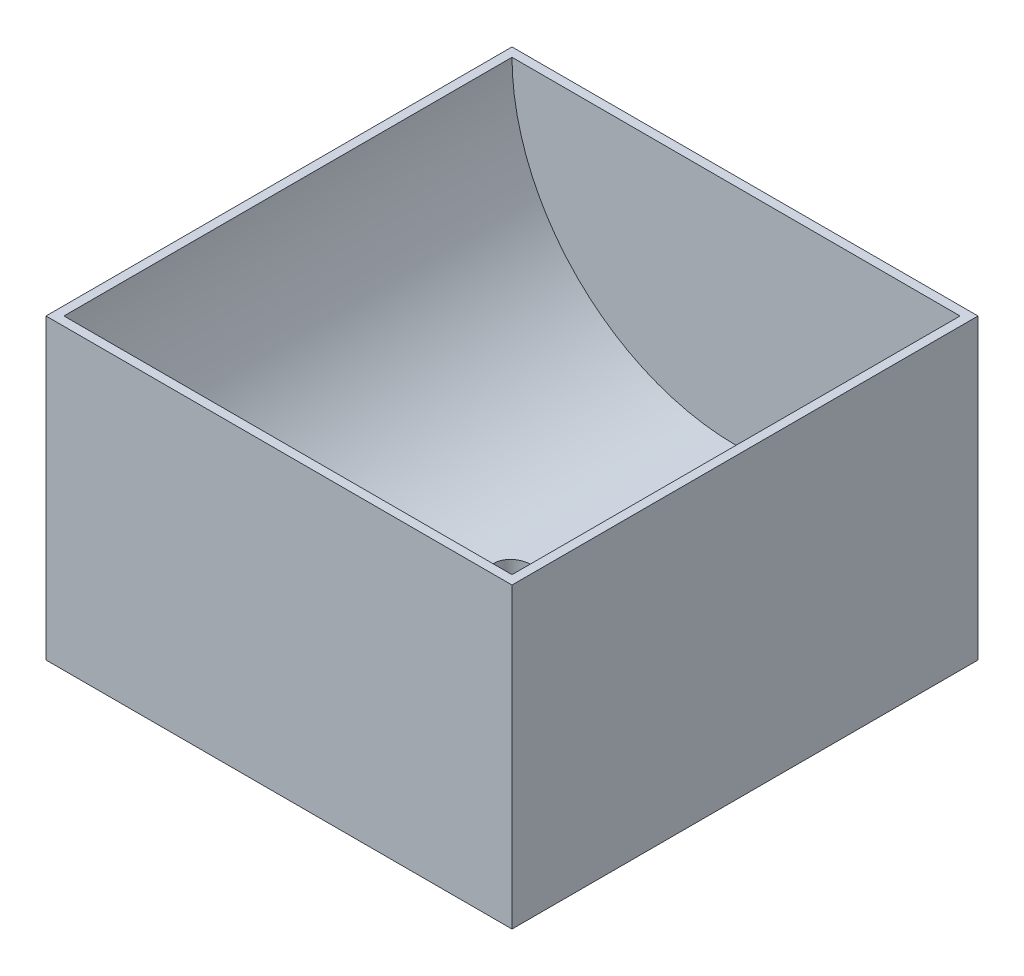
SolidWorks part; units mm, degrees
ref_plane "Front Plane" through (0, 0, 0) normal (0, 0, 1) x (1, 0, 0)
ref_plane "Top Plane" through (0, 0, 0) normal (0, 1, 0) x (1, 0, 0)
ref_plane "Right Plane" through (0, 0, 0) normal (1, 0, 0) x (0, 0, -1)
sketch "Sketch1" plane through (0, 0, 0) normal (0, 0, 1) x (1, 0, 0)
  line L0 (50, 0) -> (52, 0)
  line L1 (-52, 0) -> (-50, 0)
  line L2 (-52, 0) -> (-52, -53)
  line L3 (-52, -53) -> (52, -53)
  line L4 (52, 0) -> (52, -53)
  arc A0 (-50, 0) -> (50, 0) centre (0, 0) ccw
  dimension "D1" = 100
  dimension "D2" = 2
  dimension "D3" = 2
  dimension "D4" = 3
extrude "Boss-Extrude1" add sketch "Sketch1" along normal mid plane 100
sketch "Sketch2" plane through (0, 0, 50) normal (0, 0, 1) x (1, 0, 0)
  line L1 (-52, 0) -> (52, 0)
  line L2 (-52, 0) -> (-52, -53)
  line L3 (-52, -53) -> (52, -53)
  line L4 (52, 0) -> (52, -53)
extrude "Boss-Extrude2" add sketch "Sketch2" along normal blind 2
sketch "Sketch3" plane through (0, 0, -50) normal (0, 0, -1) x (-1, 0, 0)
  line L1 (-52, 0) -> (52, 0)
  line L2 (-52, 0) -> (-52, -53)
  line L3 (-52, -53) -> (52, -53)
  line L4 (52, 0) -> (52, -53)
extrude "Boss-Extrude3" add sketch "Sketch3" along normal blind 2
sketch "Sketch4" plane through (0, -53, 0) normal (0, -1, 0) x (1, 0, 0)
  circle A0 centre (0, 0) radius 4.05
  dimension "D1" = 8.1
extrude "Cut-Extrude2" cut sketch "Sketch4" against normal through all
sketch "Sketch5" plane through (0, -53, 0) normal (0, -1, 0) x (1, 0, 0)
  line L1 (-7.5056, 0) -> (-3.7528, -6.5)
  line L2 (-3.7528, -6.5) -> (3.7528, -6.5)
  line L3 (3.7528, -6.5) -> (7.5056, 0)
  line L4 (7.5056, 0) -> (3.7528, 6.5)
  line L5 (3.7528, 6.5) -> (-3.7528, 6.5)
  line L6 (-3.7528, 6.5) -> (-7.5056, 0)
  line L7 (-52, -52) -> (52, -52)
  line L8 (-52, -52) -> (-52, 52)
  line L9 (-52, 52) -> (52, 52)
  line L10 (52, -52) -> (52, 52)
  circle A0 centre (0, 0) radius 6.5 construction
  dimension "D1" = 13
extrude "Boss-Extrude4" add sketch "Sketch5" along normal blind 13.5
sketch "Sketch6" plane through (0, -66.5, 0) normal (0, -1, 0) x (1, 0, 0)
  circle A0 centre (0, 0) radius 8
  dimension "D1" = 16
extrude "Cut-Extrude3" cut sketch "Sketch6" against normal blind 7
